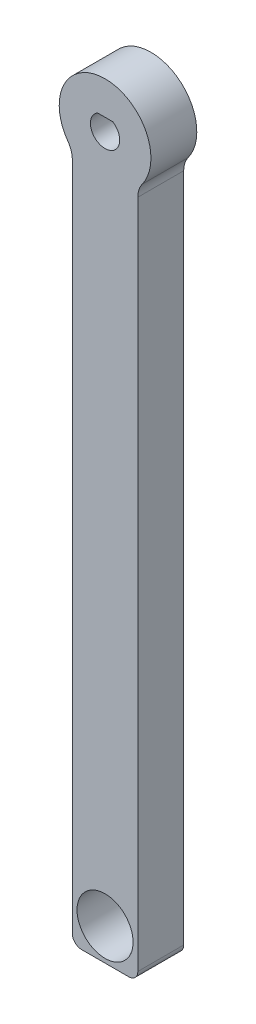
SolidWorks part; units mm, degrees
ref_plane "Front Plane" through (0, 0, 0) normal (0, 0, 1) x (1, 0, 0)
ref_plane "Top Plane" through (0, 0, 0) normal (0, 1, 0) x (1, 0, 0)
ref_plane "Right Plane" through (0, 0, 0) normal (1, 0, 0) x (0, 0, -1)
sketch "Sketch1" plane through (0, 0, 0) normal (0, 0, 1) x (1, 0, 0)
  line L0 (-1.6093, 2.52) -> (1.6093, 2.52)
  line L1 (-1.6666, 2.72) -> (1.6666, 2.72)
  arc A0 (-1.6186, 2.514) -> (1.6093, 2.52) centre (0, 0) ccw
  arc A1 (-1.6666, 2.72) -> (1.6666, 2.72) centre (0, 0) ccw
  circle A2 centre (0, 0) radius 10
  arc A3 (-1.6093, 2.52) -> (1.6093, 2.52) centre (0, 0) ccw construction
  dimension "D1" = 5.98
  dimension "D4" = 20
  dimension "D2" = 2.52
  dimension "D3" = 0.2
extrude "Boss-Extrude1" add sketch "Sketch1" along normal blind 10 contours A2 A1 L1
sketch "Sketch2" plane through (0, 0, 0) normal (0, 0, -1) x (-1, 0, 0)
  line L5 (-10, -7) -> (10, -7)
  line L6 (-10, -7) -> (-10, -10)
  line L7 (-10, -10) -> (10, -10)
  line L8 (10, -7) -> (10, -10)
  circle A1 centre (0, 0) radius 10
  circle A2 centre (0, 0) radius 10
  circle M8 centre (0, 0) radius 10
  dimension "D2" = 3
  dimension "D1" = 0
extrude "Cut-Extrude1" cut sketch "Sketch2" against normal blind 10 contours L5 M8
sketch "Sketch3" plane through (0, -7, 0) normal (0, -1, 0) x (1, 0, 0)
  line L4 (-7.1414, 0) -> (7.1414, 0)
  line L5 (7.1414, 0) -> (7.1414, 10)
  line L6 (7.1414, 10) -> (-7.1414, 10)
  line L7 (-7.1414, 10) -> (-7.1414, 0)
  line L8 (-7.1414, 0) -> (7.1414, 0)
  line L9 (7.1414, 0) -> (7.1414, 10)
  line L10 (7.1414, 10) -> (-7.1414, 10)
  line L11 (-7.1414, 10) -> (-7.1414, 0)
  dimension "D1" = 0
extrude "Boss-Extrude2" add sketch "Sketch3" along normal blind 150
sketch "Sketch4" plane through (0, 0, 0) normal (0, 0, -1) x (-1, 0, 0)
  line L0 (7.1414, -157) -> (-7.1414, -157) construction
  circle A0 centre (0, -150) radius 6.11
  dimension "D1" = 12.22
  dimension "D2" = 7
extrude "Cut-Extrude2" cut sketch "Sketch4" against normal blind 10
fillet "Fillet1" radius 5 2 edges at (-7.1414, -7, 5) (7.1414, -7, 5)
fillet "Fillet2" radius 2 2 edges at (7.1414, -157, 5) (-7.1414, -157, 5)
